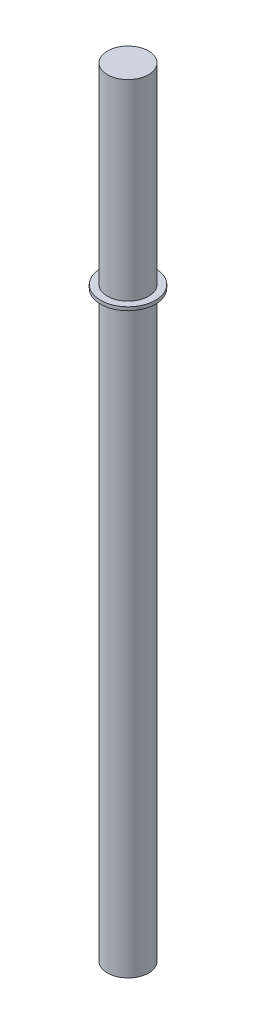
SolidWorks part; units mm, degrees
ref_plane "Front Plane" through (0, 0, 0) normal (0, 0, 1) x (1, 0, 0)
ref_plane "Top Plane" through (0, 0, 0) normal (0, 1, 0) x (1, 0, 0)
ref_plane "Right Plane" through (0, 0, 0) normal (1, 0, 0) x (0, 0, -1)
sketch "Sketch1" plane through (0, 0, 0) normal (0, 1, 0) x (1, 0, 0)
  circle A0 centre (0, 0) radius 3
extrude "Boss-Extrude1" add sketch "Sketch1" along normal blind 28
sketch "Sketch2" plane through (0, 0, 0) normal (0, -1, 0) x (1, 0, 0)
  circle A0 centre (0, 0) radius 4
extrude "Boss-Extrude2" add sketch "Sketch2" along normal blind 0.5
sketch "Sketch3" plane through (0, -0.5, 0) normal (0, -1, 0) x (1, 0, 0)
  circle A0 centre (0, 0) radius 3
extrude "Boss-Extrude3" add sketch "Sketch3" along normal blind 85
